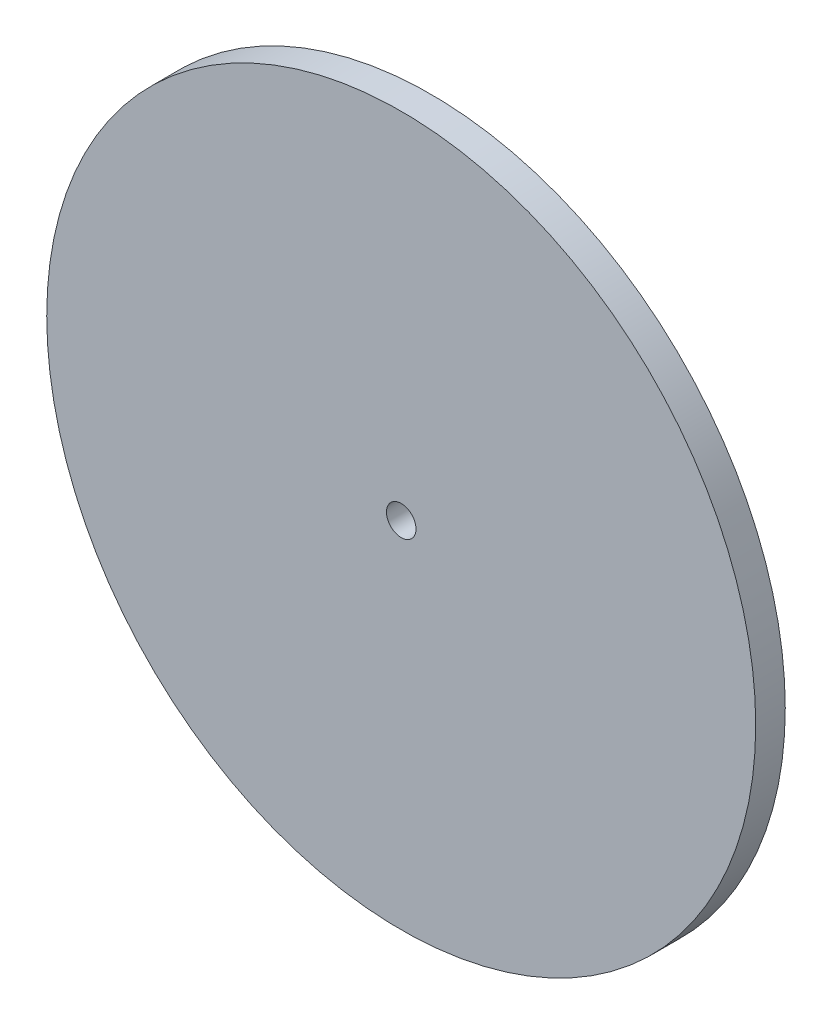
SolidWorks part; units mm, degrees
material "Maple"
ref_plane "Front Plane" through (0, 0, 0) normal (0, 0, 1) x (1, 0, 0)
ref_plane "Top Plane" through (0, 0, 0) normal (0, 1, 0) x (1, 0, 0)
ref_plane "Right Plane" through (0, 0, 0) normal (1, 0, 0) x (0, 0, -1)
sketch "Sketch1" plane through (0, 0, 0) normal (0, 0, 1) x (1, 0, 0)
  circle A0 centre (0, 0) radius 152.4
  dimension "D1" = 304.8
extrude "Boss-Extrude1" add sketch "Sketch1" along normal blind 12.7
sketch "Sketch2" plane through (0, 0, 0) normal (0, 0, -1) x (-1, 0, 0)
  circle A0 centre (0, 0) radius 6.35
  dimension "D1" = 12.7
extrude "Cut-Extrude1" cut sketch "Sketch2" against normal through all
